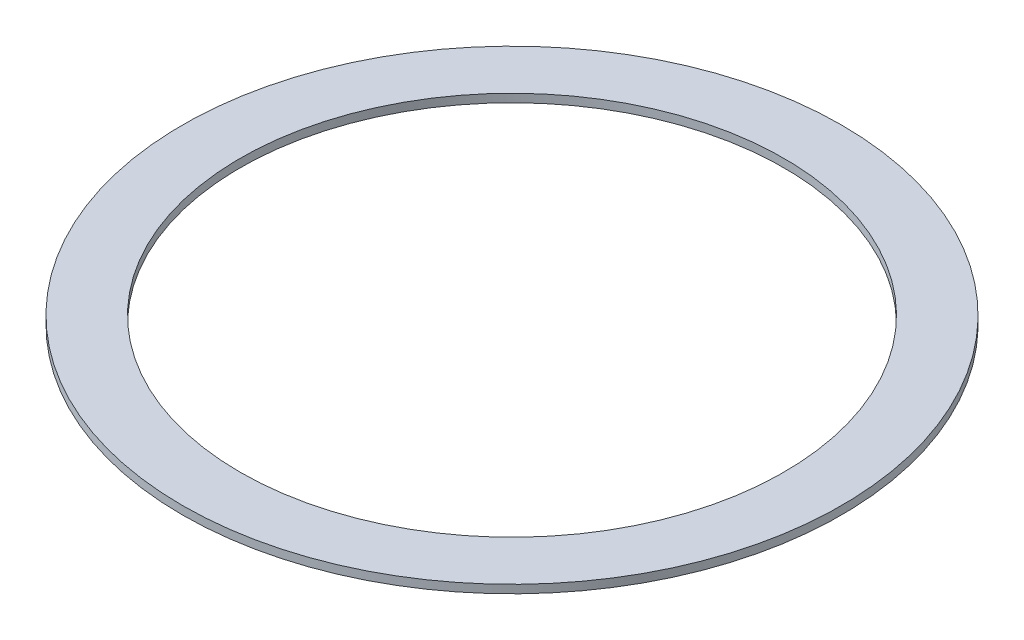
SolidWorks part; units mm, degrees
material "2.0321 (CuZn37)"
ref_plane "Płaszczyzna przednia" through (0, 0, 0) normal (0, 0, 1) x (1, 0, 0)
ref_plane "Płaszczyzna górna" through (0, 0, 0) normal (0, 1, 0) x (1, 0, 0)
ref_plane "Płaszczyzna prawa" through (0, 0, 0) normal (1, 0, 0) x (0, 0, -1)
sketch "Szkic1" plane through (0, 0, 0) normal (0, 1, 0) x (1, 0, 0)
  circle A0 centre (0, 0) radius 33
  circle A1 centre (0, 0) radius 40
  dimension "D1" = 66
  dimension "D2" = 80
extrude "Dodanie-wyciągnięcie1" add sketch "Szkic1" along normal blind 1
